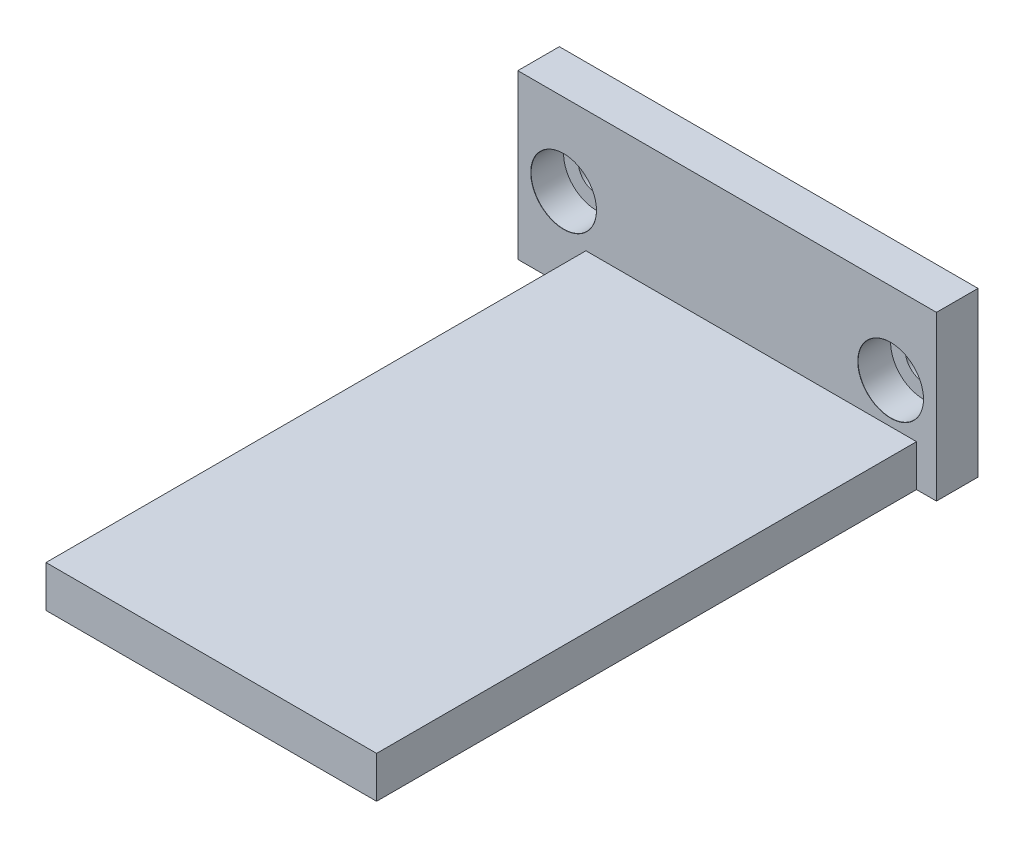
SolidWorks part; units mm, degrees
ref_plane "Front" through (0, 0, 0) normal (0, 0, 1) x (1, 0, 0)
ref_plane "Top" through (0, 0, 0) normal (0, 1, 0) x (1, 0, 0)
ref_plane "Right" through (0, 0, 0) normal (1, 0, 0) x (0, 0, -1)
sketch "Sketch1" plane through (0, 0, 0) normal (0, 0, 1) x (1, 0, 0)
  line L1 (0, 0) -> (64.008, 0)
  line L2 (0, 0) -> (0, 24.9936)
  line L3 (0, 24.9936) -> (64.008, 24.9936)
  line L4 (64.008, 0) -> (64.008, 24.9936)
  dimension "D1" = 24.9936
  dimension "D2" = 64.008
extrude "Boss-Extrude1" add sketch "Sketch1" along normal blind 6.35
sketch "Sketch2" plane through (0, 0, 6.35) normal (0, 0, 1) x (1, 0, 0)
  line L0 (64.008, 0) -> (64.008, 24.9936) construction
  line L1 (0, 0) -> (64.008, 0)
  line L2 (0, 0) -> (0, 6.35)
  line L3 (0, 6.35) -> (64.008, 6.35)
  line L4 (64.008, 0) -> (64.008, 6.35)
  dimension "D1" = 6.35
extrude "Boss-Extrude2" add sketch "Sketch2" along normal blind 82.55
sketch "Sketch5" plane through (0, 0, 6.35) normal (0, 0, 1) x (1, 0, 0)
  line L0 (-2.4403, 12.5) -> (65.3922, 12.5) construction
  line L1 (0, 0) -> (64.008, 0) construction
  line L2 (7, 27.9859) -> (7, -6.3192) construction
  line L3 (57, 30.103) -> (57, -4.1589) construction
  line L4 (0, 24.9936) -> (0, 6.35) construction
  dimension "D1" = 12.5
  dimension "D2" = 50
  dimension "D3" = 7
hole_wizard "CBORE for M5 SHCS1" positions "Sketch6" profile "Sketch7" counterbore size "M5" standard "ANSI Metric" end condition up to next
sketch "Sketch6" plane through (0, 0, 6.35) normal (0, 0, 1) x (1, 0, 0)
  line L0 (-2.4403, 12.5) -> (65.3922, 12.5) construction
  line L1 (7, 27.9859) -> (7, -6.3192) construction
  line L2 (57, 30.103) -> (57, -4.1589) construction
  point P0 (7, 12.5)
  point P6 (57, 12.5)
sketch "Sketch7" plane through (7, 12.5, 6.35) normal (1, 0, 0) x (0, -1, 0)
  line L0 (0, 0) -> (0, 6.35)
  line L1 (0, 6.35) -> (2.75, 6.35)
  line L3 (2.75, 6.35) -> (2.75, 5)
  line L4 (5, 5) -> (2.75, 5)
  line L5 (5, 5) -> (5, 0.025)
  line L6 (5, 0.025) -> (5.025, 0)
  line L7 (5.025, 0) -> (0, 0)
  line L8 (-5, 0.025) -> (-5.025, 0) construction
  line L11 (0, -6.35) -> (0, 107.95) construction
  dimension "Thru Hole Dia." = 5.5
  dimension "Thru Hole Depth" = 6.35
  dimension "C'Bore Dia." = 10
  dimension "C'Bore Depth" = 5
  dimension "Near C'Sink Dia." = 10.05
  dimension "Near C'Sink Angle" = 90
sketch "Sketch8" plane through (0, 6.35, 0) normal (0, 1, 0) x (1, 0, 0)
  line L0 (-2.4403, -6.35) -> (65.3922, -6.35) construction
  line L1 (0, -88.9) -> (10.414, -88.9)
  line L2 (0, -88.9) -> (0, -6.35)
  line L3 (0, -6.35) -> (10.414, -6.35)
  line L4 (10.414, -88.9) -> (10.414, -6.35)
  dimension "D1" = 10.414
extrude "Cut-Extrude1" cut sketch "Sketch8" against normal through all
sketch "Sketch9" plane through (0, 6.35, 0) normal (0, 1, 0) x (1, 0, 0)
  line L0 (-2.4403, -6.35) -> (65.3922, -6.35) construction
  line L1 (64.008, -88.9) -> (60.96, -88.9)
  line L2 (64.008, -88.9) -> (64.008, -6.35)
  line L3 (64.008, -6.35) -> (60.96, -6.35)
  line L4 (60.96, -88.9) -> (60.96, -6.35)
  dimension "D1" = 3.048
extrude "Cut-Extrude3" cut sketch "Sketch9" against normal through all
